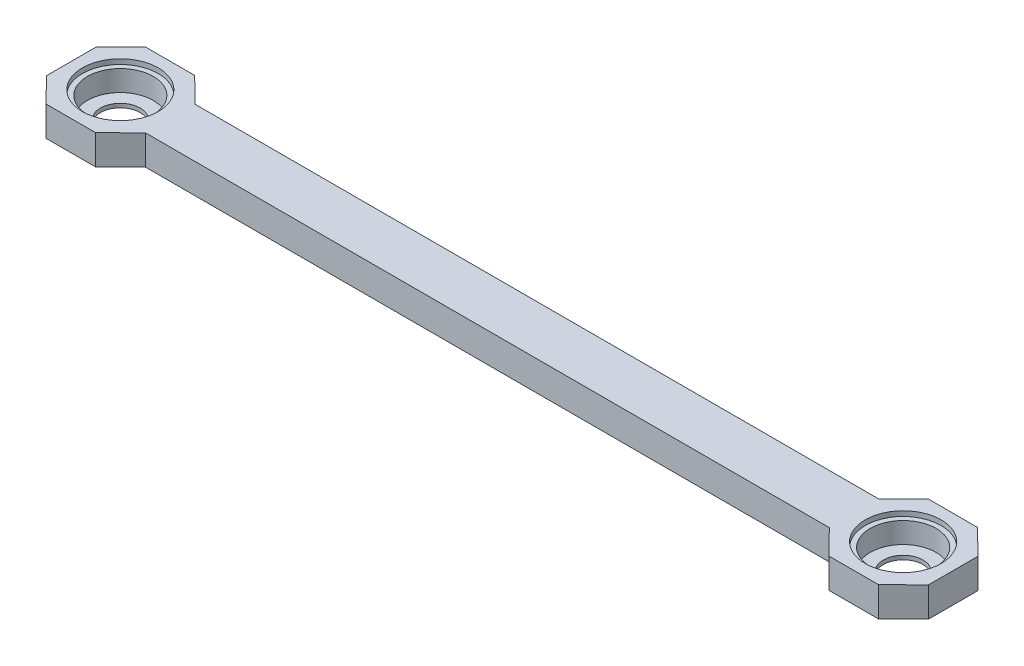
SolidWorks part; units mm, degrees
ref_plane "前视基准面" through (0, 0, 0) normal (0, 0, 1) x (1, 0, 0)
ref_plane "上视基准面" through (0, 0, 0) normal (0, 1, 0) x (1, 0, 0)
ref_plane "右视基准面" through (0, 0, 0) normal (1, 0, 0) x (0, 0, -1)
sketch "草图1" plane through (0, 0, 0) normal (0, 1, 0) x (1, 0, 0)
  line L0 (-56.1468, 0) -> (96.1142, 0) construction
  line L9 (-65.2623, 5) -> (-70.3633, 10)
  line L10 (-70.3633, 10) -> (-80.3633, 10)
  line L19 (-80.3633, 10) -> (-85.2623, 5)
  line L20 (-85.2623, 5) -> (-85.2623, -5)
  line L23 (72.7377, 5) -> (77.6367, 10)
  line L24 (77.6367, 10) -> (87.6367, 10)
  line L25 (87.6367, 10) -> (92.7398, 5)
  line L26 (92.7398, 5) -> (92.7398, -5)
  line L27 (-75.3633, 10) -> (-75.3633, -5.1974) construction
  line L28 (82.6367, 10) -> (82.6367, -7.8958) construction
  line L29 (-65.2623, -5) -> (-70.3633, -10)
  line L30 (-70.3633, -10) -> (-80.3633, -10)
  line L31 (-80.3633, -10) -> (-85.2623, -5)
  line L32 (87.6367, -10) -> (92.7398, -5)
  line L33 (77.6367, -10) -> (87.6367, -10)
  line L34 (72.7377, -5) -> (77.6367, -10)
  line L35 (-65.2623, 5) -> (72.7377, 5)
  line L36 (72.7377, -5) -> (-65.2623, -5)
  circle A0 centre (-75.3633, 0) radius 4
  circle A2 centre (82.6367, 0) radius 4
  point P18 (-27.2623, 0)
  point P24 (-85.2623, 0)
  point P25 (92.7398, 0)
  point P28 (72.7377, 0)
  dimension "D1" = 158
  dimension "D2" = 10
  dimension "D11" = 8
  dimension "D12" = 8
  dimension "D3" = 5
  dimension "D4" = 20.0021
  dimension "D5" = 10
  dimension "D6" = 7
  dimension "D7" = 10
  dimension "D8" = 7
  dimension "D9" = 10
  dimension "D10" = 5
  dimension "D13" = 20
extrude "凸台-拉伸1" add sketch "草图1" along normal blind 6
sketch "草图2" plane through (0, 6, 0) normal (0, 1, 0) x (1, 0, 0)
  circle A0 centre (82.6367, 0) radius 6.65
  circle A1 centre (-75.3633, 0) radius 6.65
  dimension "D1" = 13.3
extrude "切除-拉伸1" cut sketch "草图2" against normal blind 5.2
sketch "草图3" plane through (0, 6, 0) normal (0, 1, 0) x (1, 0, 0)
  circle A0 centre (82.6367, 0) radius 7.65
  circle A1 centre (-75.3633, 0) radius 7.65
  dimension "D1" = 15.3
extrude "切除-拉伸2" cut sketch "草图3" against normal blind 1
